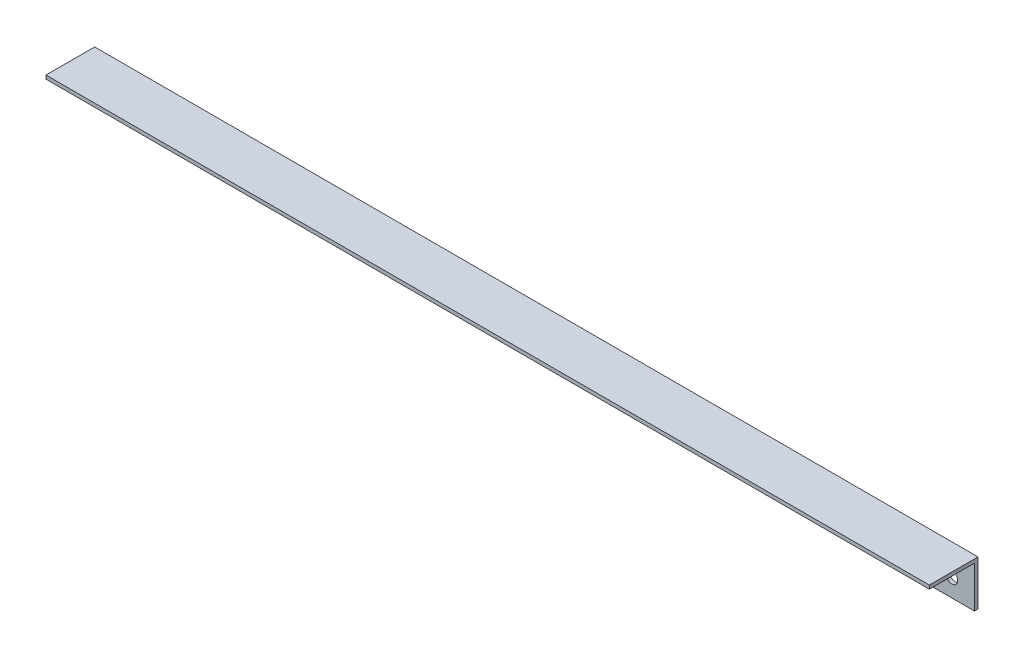
SolidWorks part; units mm, degrees
ref_plane "前视" through (0, 0, 0) normal (0, 0, 1) x (1, 0, 0)
ref_plane "上视" through (0, 0, 0) normal (0, 1, 0) x (1, 0, 0)
ref_plane "右视" through (0, 0, 0) normal (1, 0, 0) x (0, 0, -1)
sketch "草图1" plane through (0, 0, 0) normal (0, 0, 1) x (1, 0, 0)
  line L0 (0, 0) -> (0, 145.6903) construction
  line L1 (-980, 94.5121) -> (980, 94.5121)
  line L2 (-980, 94.5121) -> (-980, -5.4879)
  line L3 (-980, -5.4879) -> (980, -5.4879)
  line L4 (980, 94.5121) -> (980, -5.4879)
  line L5 (930, 34.5121) -> (-270, 34.5121) construction
  circle A0 centre (930, 34.5121) radius 13
  circle A1 centre (850, 34.5121) radius 13
  circle A2 centre (770, 34.5121) radius 13
  circle A3 centre (330, 34.5121) radius 13
  circle A4 centre (250, 34.5121) radius 13
  circle A5 centre (-770, 34.5121) radius 13
  circle A6 centre (-850, 34.5121) radius 13
  circle A7 centre (170, 34.5121) radius 13
  circle A8 centre (-170, 34.5121) radius 13
  circle A9 centre (-250, 34.5121) radius 13
  circle A10 centre (-330, 34.5121) radius 13
  circle A11 centre (-930, 34.5121) radius 13
  dimension "D6" = 26
  dimension "D8" = 440
  dimension "D10" = 80
  dimension "D1" = 1960
  dimension "D2" = 100
  dimension "D3" = 80
  dimension "D4" = 40
  dimension "D5" = 50
  dimension "D7" = 80
  dimension "D9" = 94.5121
  dimension "D11" = 80
extrude "基体-拉伸" add sketch "草图1" along normal blind 8
sketch "草图2" plane through (0, 0, 8) normal (0, 0, 1) x (1, 0, 0)
  line L0 (0, 0) -> (0, 140.4626) construction
  line L3 (-980, 94.5121) -> (980, 94.5121)
  line L4 (-980, 94.5121) -> (-980, 86.5121)
  line L5 (-980, 86.5121) -> (980, 86.5121)
  line L6 (980, 94.5121) -> (980, 86.5121)
  dimension "D1" = 1960
  dimension "D2" = 8
extrude "凸台-拉伸1" add sketch "草图2" along normal blind 100
